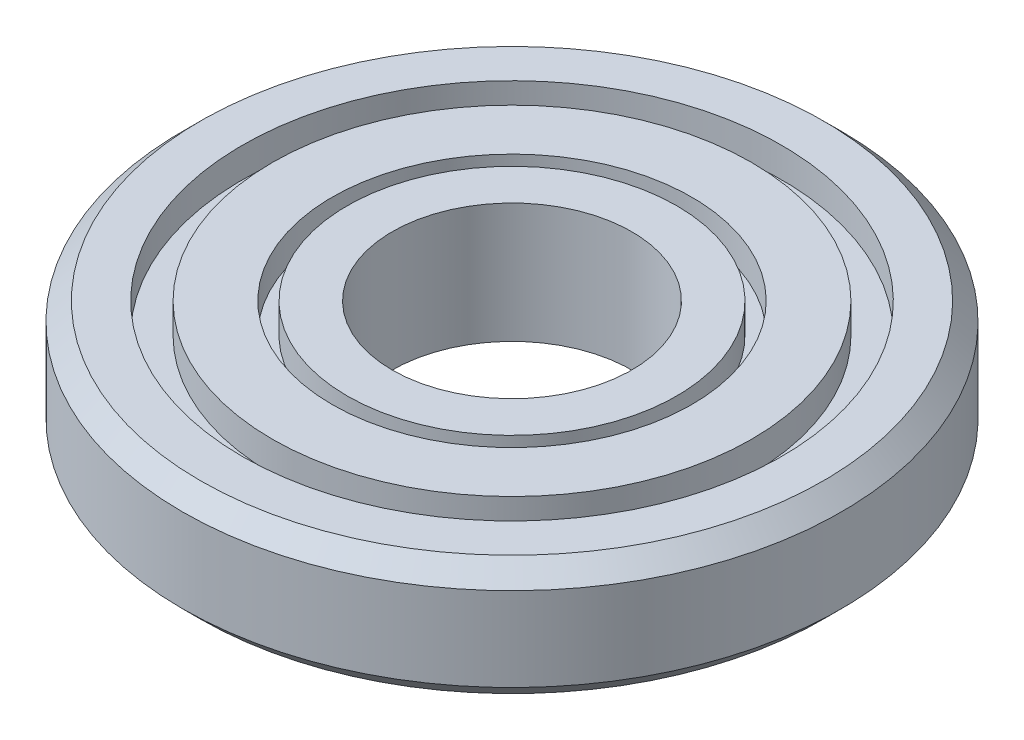
SolidWorks part; units mm, degrees
material "Stainless Steel (ferritic)"
ref_plane "Front Plane" through (0, 0, 0) normal (0, 0, 1) x (1, 0, 0)
ref_plane "Top Plane" through (0, 0, 0) normal (0, 1, 0) x (1, 0, 0)
ref_plane "Right Plane" through (0, 0, 0) normal (1, 0, 0) x (0, 0, -1)
sketch "Sketch1" plane through (0, 0, 0) normal (0, 1, 0) x (1, 0, 0)
  circle A0 centre (0, 0) radius 5.5
  circle A1 centre (0, 0) radius 2
extrude "Boss-Extrude1" add sketch "Sketch1" along normal blind 2
sketch "Sketch2" plane through (0, 2, 0) normal (0, 1, 0) x (1, 0, 0)
  circle A0 centre (0, 0) radius 4
  circle A1 centre (0, 0) radius 4.5
  circle A2 centre (0, 0) radius 3
  circle A3 centre (0, 0) radius 2.75
extrude "Cut-Extrude1" cut sketch "Sketch2" against normal blind 0.5 contours A2 A3 | A1 A0
sketch "Sketch3" plane through (0, 0, 0) normal (0, -1, 0) x (1, 0, 0)
  circle A0 centre (0, 0) radius 2.75
  circle A1 centre (0, 0) radius 3
  circle A2 centre (0, 0) radius 4
  circle A3 centre (0, 0) radius 4.5
extrude "Cut-Extrude2" cut sketch "Sketch3" against normal blind 0.5 contours A3 A2 | A1 A0
chamfer "Chamfer1" distance 0.3 angle 45 2 edges at (0, 2, 5.5) (0, 0, 5.5)
